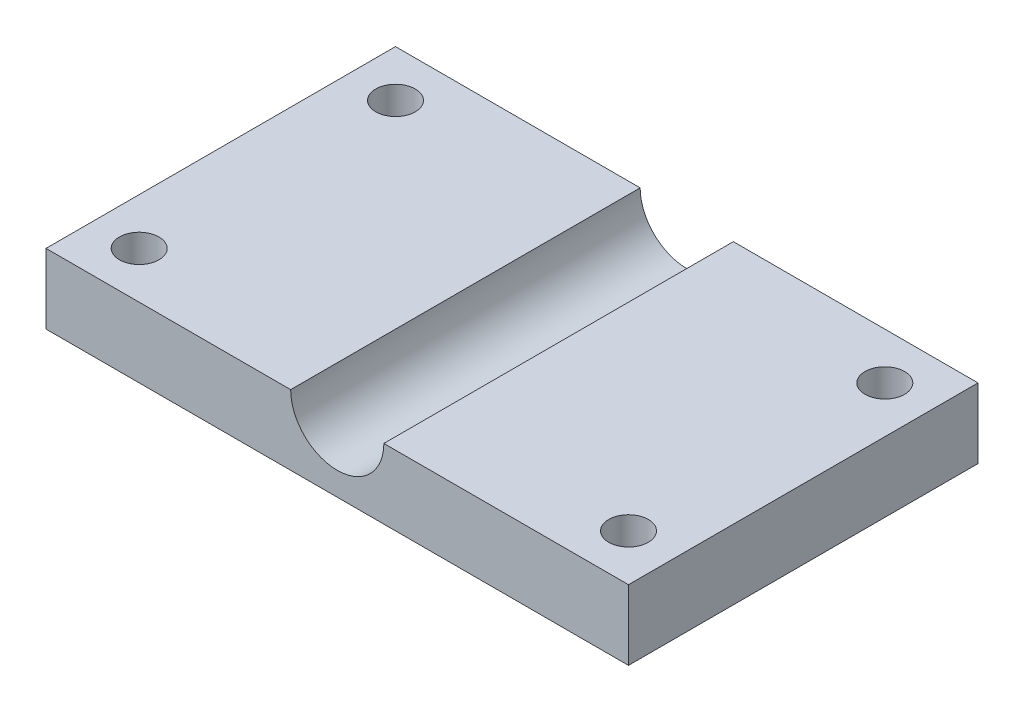
SolidWorks part; units mm, degrees
ref_plane "Piano frontale" through (0, 0, 0) normal (0, 0, 1) x (1, 0, 0)
ref_plane "Piano superiore" through (0, 0, 0) normal (0, 1, 0) x (1, 0, 0)
ref_plane "Piano destro" through (0, 0, 0) normal (1, 0, 0) x (0, 0, -1)
sketch "Schizzo1" plane through (0, 0, 0) normal (0, 1, 0) x (1, 0, 0)
  line L1 (-21.7437, 15.7035) -> (28.2563, 15.7035)
  line L2 (-21.7437, 15.7035) -> (-21.7437, -14.2965)
  line L3 (-21.7437, -14.2965) -> (28.2563, -14.2965)
  line L4 (28.2563, 15.7035) -> (28.2563, -14.2965)
  dimension "D1" = 50
  dimension "D2" = 30
extrude "Estrusione-Estrusione1" add sketch "Schizzo1" along normal blind 6
sketch "Schizzo2" plane through (0, 0, 14.2965) normal (0, 0, 1) x (1, 0, 0)
  line L0 (-21.7437, 6) -> (28.2563, 6) construction
  circle A0 centre (3.2563, 6) radius 4
  dimension "D1" = 8
extrude "Taglio-Estrusione1" cut sketch "Schizzo2" against normal through all
sketch "Schizzo3" plane through (0, 0, 0) normal (0, -1, 0) x (1, 0, 0)
  line L0 (-21.7437, 14.2965) -> (28.2563, 14.2965) construction
  line L1 (-21.7437, -15.7035) -> (-21.7437, 14.2965) construction
  line L2 (3.2563, 14.2965) -> (3.2563, -15.7035) construction
  line L3 (28.2563, -15.7035) -> (-21.7437, -15.7035) construction
  line L4 (-21.7437, -0.7035) -> (28.2563, -0.7035) construction
  line L5 (28.2563, 14.2965) -> (28.2563, -15.7035) construction
  circle A0 centre (-17.7437, 10.2965) radius 1.7
  circle A1 centre (24.2563, 10.2965) radius 1.7
  circle A2 centre (24.2563, -11.7035) radius 1.7
  circle A3 centre (-17.7437, -11.7035) radius 1.7
  dimension "D1" = 3.4
  dimension "D2" = 4
  dimension "D3" = 4
extrude "Taglio-Estrusione2" cut sketch "Schizzo3" against normal blind 10
